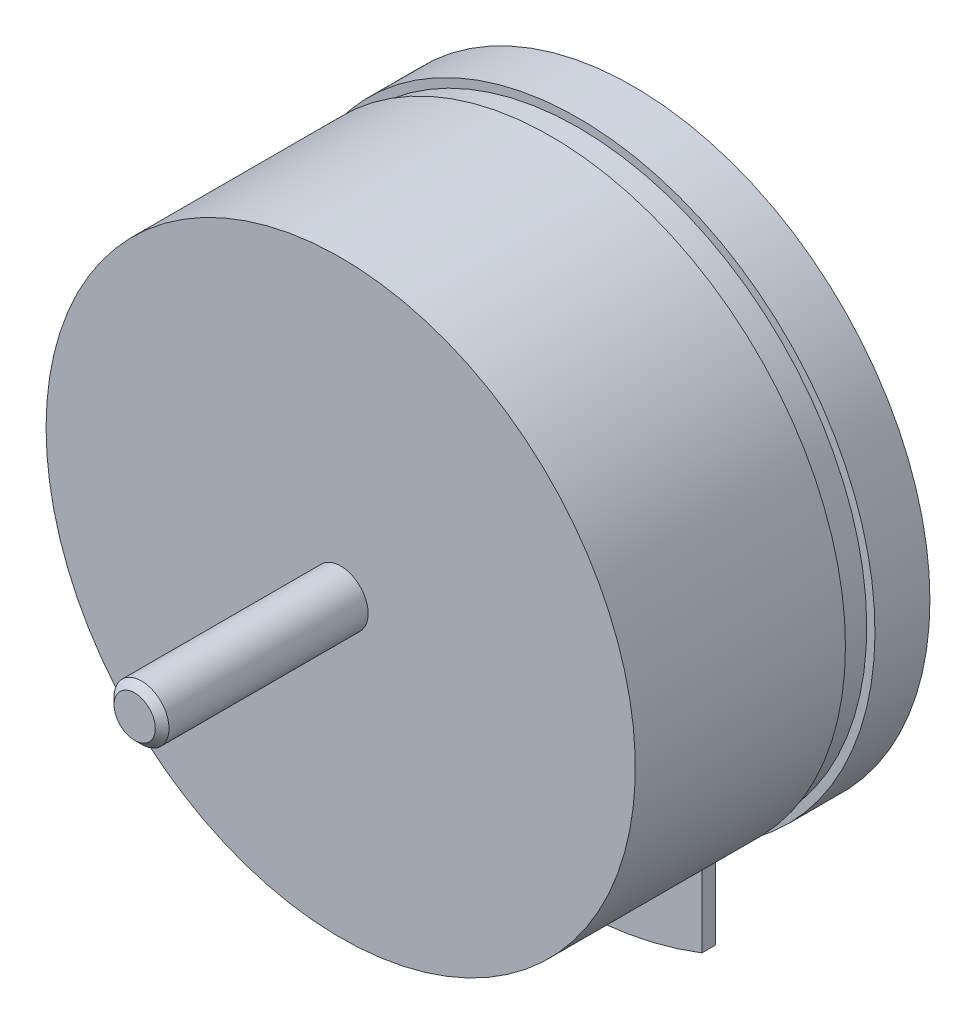
SolidWorks part; units mm, degrees
ref_plane "前视基准面" through (0, 0, 0) normal (0, 0, 1) x (1, 0, 0)
ref_plane "上视基准面" through (0, 0, 0) normal (0, 1, 0) x (1, 0, 0)
ref_plane "右视基准面" through (0, 0, 0) normal (1, 0, 0) x (0, 0, -1)
sketch "草图1" plane through (0, 0, 0) normal (0, 0, 1) x (1, 0, 0)
  circle A0 centre (0, 0) radius 21.6
  dimension "D1" = 43.2
extrude "拉伸1" add sketch "草图1" along normal blind 4
sketch "草图6" plane through (0, 0, 0) normal (0, 0, -1) x (-1, 0, 0)
  circle A0 centre (0, 0) radius 21.45
  dimension "D1" = 42.9
extrude "拉伸6" add sketch "草图6" against normal blind 21.3
sketch "草图2" plane through (0, 0, 21.3) normal (0, 0, 1) x (1, 0, 0)
  circle A0 centre (0, 0) radius 2
  dimension "D1" = 4
extrude "拉伸2" add sketch "草图2" along normal blind 15
sketch "草图3" plane through (0, 0, 0) normal (0, 0, -1) x (-1, 0, 0)
  line L0 (0, 0) -> (0, 11) construction
  circle A0 centre (0, 0) radius 11 construction
  circle A1 centre (0, 11) radius 1.25
  dimension "D1" = 22
  dimension "D2" = 2.5
extrude "拉伸3" cut sketch "草图3" against normal blind 3.9
cosmetic thread "装饰螺纹线1" parameters "D2"=3
pattern_circular "阵列(圆周)1" count 3 over 360 about axis through (0, 0, 0) along (0, 0, 1) of "拉伸3"
sketch "草图4" plane through (0, 0, 0) normal (0, 0, -1) x (-1, 0, 0)
  circle A0 centre (0, 0) radius 6
  dimension "D1" = 12
extrude "拉伸4" add sketch "草图4" along normal blind 3.2
sketch "草图5" plane through (0, 0, -3.2) normal (0, 0, -1) x (-1, 0, 0)
  circle A0 centre (0, 0) radius 2
  dimension "D1" = 4
extrude "拉伸5" add sketch "草图5" along normal blind 7.8
sketch "草图7" plane through (0, 0, 4) normal (0, 0, 1) x (1, 0, 0)
  circle A0 centre (0, 0) radius 21
  circle A1 centre (0, 0) radius 21.45
  circle A2 centre (0, 0) radius 21.45
  dimension "D2" = 42
  dimension "D1" = 0
extrude "拉伸7" cut sketch "草图7" along normal blind 2
sketch "草图9" plane through (0, 0, 4) normal (0, 0, 1) x (1, 0, 0)
  line L0 (0, 0) -> (0, -18.4662) construction
  line L1 (-10, -18.4662) -> (10, -18.4662)
  line L2 (-10, -18.4662) -> (-10, -25.5453)
  line L4 (10, -18.4662) -> (10, -25.5453)
  circle A0 centre (0, 0) radius 21 construction
  arc A1 (-10, -25.5453) -> (10, -25.5453) centre (0, 0) ccw
  point P1 (9.5463, -20.414)
  dimension "D1" = 20
extrude "拉伸9" add sketch "草图9" along normal blind 1
chamfer "倒角1" distance 0.5 angle 45 2 edges at (-2, 0, -11) (2, 0, 36.3)
